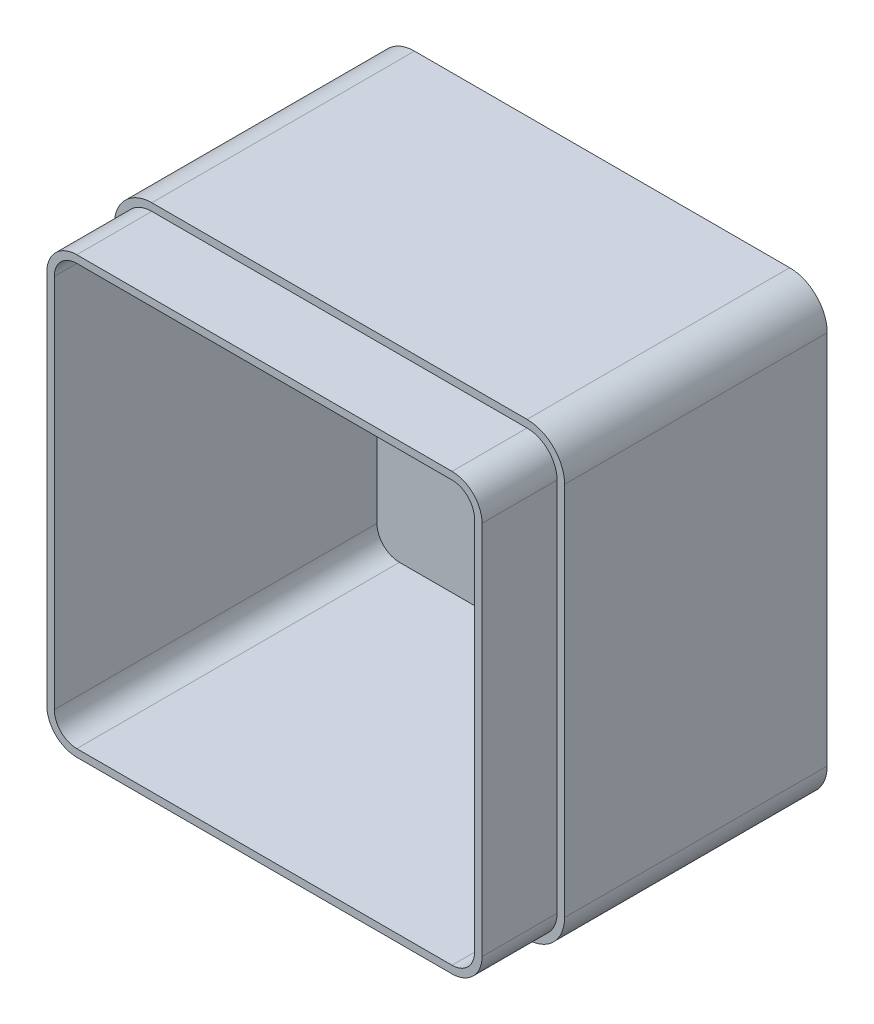
SolidWorks part; units mm, degrees
ref_plane "Alzado" through (0, 0, 0) normal (0, 0, 1) x (1, 0, 0)
ref_plane "Planta" through (0, 0, 0) normal (0, 1, 0) x (1, 0, 0)
ref_plane "Vista lateral" through (0, 0, 0) normal (1, 0, 0) x (0, 0, -1)
sketch "Croquis1" plane through (0, 0, 0) normal (0, 0, 1) x (1, 0, 0)
  line L1 (0, 0) -> (120, 0)
  line L2 (0, 0) -> (0, 120)
  line L3 (0, 120) -> (120, 120)
  line L4 (120, 0) -> (120, 120)
  dimension "D1" = 120
  dimension "D2" = 120
extrude "Saliente-Extruir1" add sketch "Croquis1" along normal blind 90
fillet "Redondeo2" radius 10 4 edges at (120, 120, 45) (0, 120, 45) (120, 0, 45) (0, 0, 45)
shell "Vaciado2" thickness 4
sketch "Croquis7" plane through (0, 0, 90) normal (0, 0, 1) x (1, 0, 0)
  line L0 (2, 110) -> (2, 10)
  line L1 (10, 2) -> (110, 2)
  line L2 (118, 10) -> (118, 110)
  line L3 (110, 118) -> (10, 118)
  line L4 (120, 10) -> (120, 110)
  line L5 (110, 120) -> (10, 120)
  line L6 (0, 110) -> (0, 10)
  line L7 (10, 0) -> (110, 0)
  line L8 (120, 10) -> (120, 110)
  line L9 (110, 120) -> (10, 120)
  line L10 (0, 110) -> (0, 10)
  line L11 (10, 0) -> (110, 0)
  arc A0 (10, 118) -> (2, 110) centre (10, 110) ccw
  arc A1 (2, 10) -> (10, 2) centre (10, 10) ccw
  arc A2 (110, 2) -> (118, 10) centre (110, 10) ccw
  arc A3 (118, 110) -> (110, 118) centre (110, 110) ccw
  arc A4 (120, 110) -> (110, 120) centre (110, 110) ccw
  arc A5 (10, 120) -> (0, 110) centre (10, 110) ccw
  arc A6 (0, 10) -> (10, 0) centre (10, 10) ccw
  arc A7 (110, 0) -> (120, 10) centre (110, 10) ccw
  arc A8 (120, 110) -> (110, 120) centre (110, 110) ccw
  arc A9 (10, 120) -> (0, 110) centre (10, 110) ccw
  arc A10 (0, 10) -> (10, 0) centre (10, 10) ccw
  arc A11 (110, 0) -> (120, 10) centre (110, 10) ccw
  dimension "D1" = 0
  dimension "D2" = 2
extrude "Cortar-Extruir2" cut sketch "Croquis7" against normal blind 20
